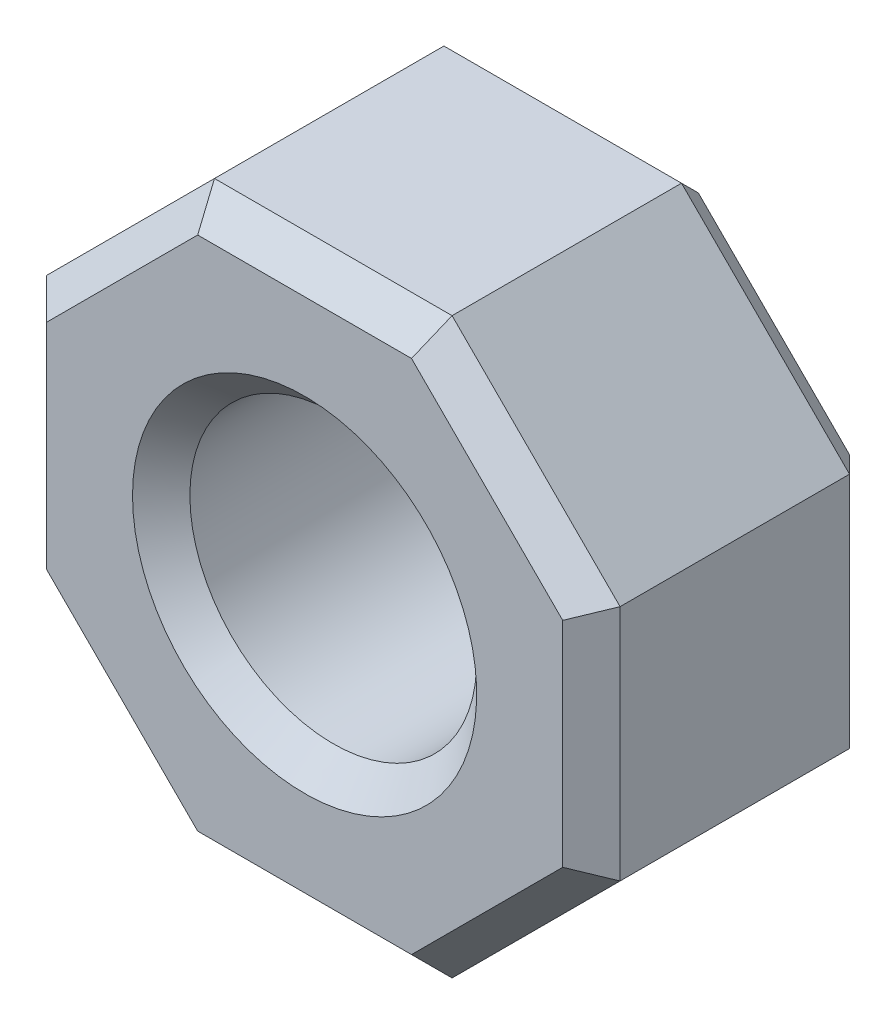
SolidWorks part; units mm, degrees
ref_plane "Front Plane" through (0, 0, 0) normal (0, 0, 1) x (1, 0, 0)
ref_plane "Top Plane" through (0, 0, 0) normal (0, 1, 0) x (1, 0, 0)
ref_plane "Right Plane" through (0, 0, 0) normal (1, 0, 0) x (0, 0, -1)
sketch "Sketch2" plane through (0, 0, 0) normal (0, 0, 1) x (1, 0, 0)
  line L0 (-25, 10.3553) -> (-10.3553, 25)
  line L1 (-10.3553, 25) -> (10.3553, 25)
  line L2 (10.3553, 25) -> (25, 10.3553)
  line L3 (25, 10.3553) -> (25, -10.3553)
  line L4 (25, -10.3553) -> (10.3553, -25)
  line L5 (10.3553, -25) -> (-10.3553, -25)
  line L6 (-10.3553, -25) -> (-25, -10.3553)
  line L7 (-25, -10.3553) -> (-25, 10.3553)
  circle A0 centre (0, 0) radius 12.5
  dimension "D1" = 25
  dimension "D2" = 135
  dimension "D3" = 135
  dimension "D4" = 135
  dimension "D5" = 25
  dimension "D6" = 25
extrude "Extrude2" add sketch "Sketch2" along normal blind 25
chamfer "Chamfer3" distance 2.5 angle 45 9 edges at (12.5, 0, 0) (-17.6777, 17.6777, 0) (-25, 0, 0) (-17.6777, -17.6777, 0) (0, -25, 0) (17.6777, -17.6777, 0) (25, 0, 0) (17.6777, 17.6777, 0) (0, 25, 0)
chamfer "Chamfer4" distance 2.5 angle 45 9 edges at (12.5, 0, 25) (17.6777, 17.6777, 25) (25, 0, 25) (17.6777, -17.6777, 25) (0, -25, 25) (-17.6777, -17.6777, 25) (-25, 0, 25) (-17.6777, 17.6777, 25) (0, 25, 25)
